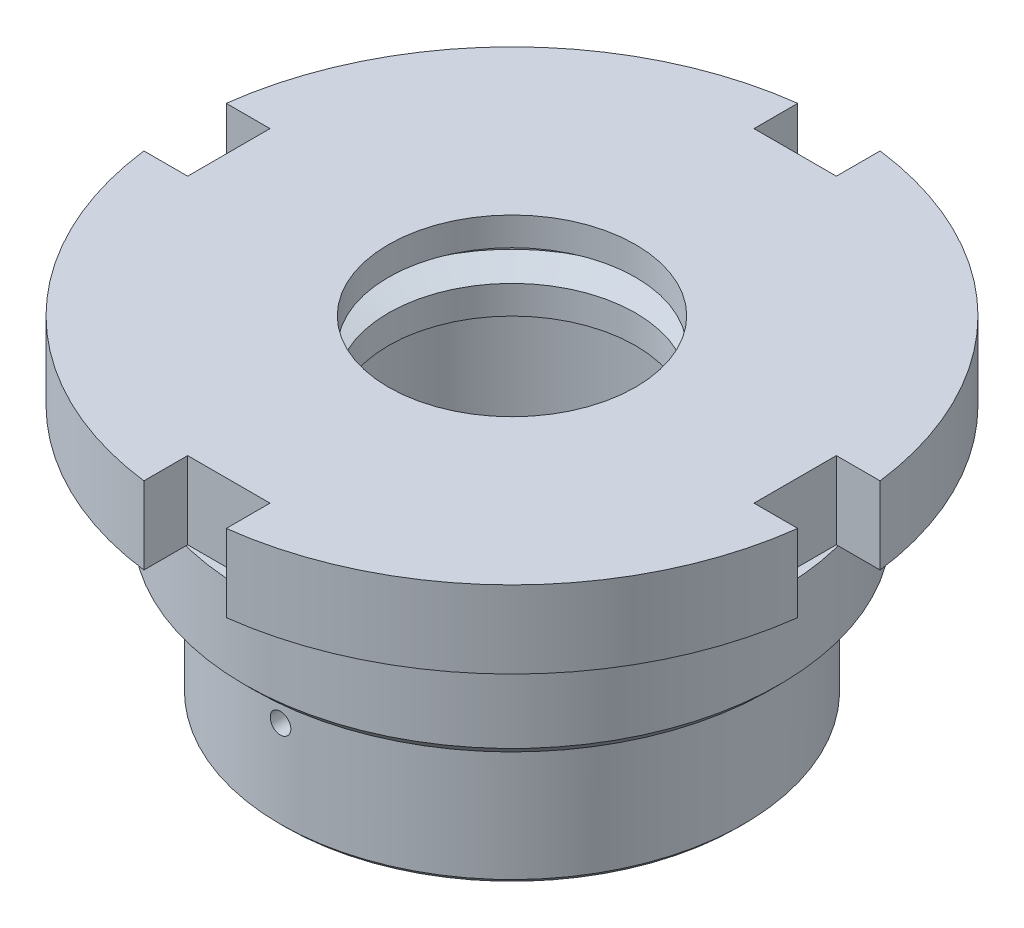
SolidWorks part; units mm, degrees
material "1023 Листовая углеродистая сталь (SS)"
ref_plane "Спереди" through (0, 0, 0) normal (0, 0, 1) x (1, 0, 0)
ref_plane "Сверху" through (0, 0, 0) normal (0, 1, 0) x (1, 0, 0)
ref_plane "Справа" through (0, 0, 0) normal (1, 0, 0) x (0, 0, -1)
ref_plane "Плоскость4" through (0, 0, 0) normal (0, 0, -1) x (-1, 0, 0)
sketch "Эскиз1" plane through (0, 0, 0) normal (0, 0, -1) x (-1, 0, 0)
  line L0 (-64, 49) -> (0, 49)
  line L1 (0, 49) -> (0, 64)
  line L2 (0, 64) -> (-64, 64)
  line L3 (-64, 64) -> (-64, 49)
  line L4 (0, 49) -> (0, 64) construction
revolve "Повернуть1" add sketch "Эскиз1" angle 360 about L4
sketch "Эскиз2" plane through (0, 64, 0) normal (0, 1, 0) x (-1, 0, 0)
  line L0 (63.498, 8) -> (55, 8)
  line L1 (55, 8) -> (55, -8)
  line L2 (55, -8) -> (63.498, -8)
  arc A0 (63.498, -8) -> (63.498, 8) centre (0, 0) ccw
extrude "Вырез-Вытянуть1" cut sketch "Эскиз2" against normal through all
sketch "Эскиз3" plane through (0, 64, 0) normal (0, 1, 0) x (-1, 0, 0)
  line L0 (8, -63.498) -> (8, -55)
  line L1 (8, -55) -> (-8, -55)
  line L2 (-8, -55) -> (-8, -63.498)
  arc A0 (-8, -63.498) -> (8, -63.498) centre (0, 0) ccw
extrude "Вырез-Вытянуть2" cut sketch "Эскиз3" against normal through all
sketch "Эскиз4" plane through (0, 64, 0) normal (0, 1, 0) x (-1, 0, 0)
  line L0 (-63.498, -8) -> (-55, -8)
  line L1 (-55, -8) -> (-55, 8)
  line L2 (-55, 8) -> (-63.498, 8)
  arc A0 (-63.498, 8) -> (-63.498, -8) centre (0, 0) ccw
extrude "Вырез-Вытянуть3" cut sketch "Эскиз4" against normal through all
sketch "Эскиз5" plane through (0, 64, 0) normal (0, 1, 0) x (-1, 0, 0)
  line L0 (-8, 63.498) -> (-8, 55)
  line L1 (-8, 55) -> (8, 55)
  line L2 (8, 55) -> (8, 63.498)
  arc A0 (8, 63.498) -> (-8, 63.498) centre (0, 0) ccw
extrude "Вырез-Вытянуть4" cut sketch "Эскиз5" against normal through all
sketch "Эскиз6" plane through (0, 0, 0) normal (0, 0, -1) x (-1, 0, 0)
  line L0 (-45, 0) -> (0, 0)
  line L1 (0, 0) -> (0, 49)
  line L2 (0, 49) -> (-48, 49)
  line L3 (-48, 49) -> (-48, 44)
  line L4 (-48, 44) -> (-52, 44)
  line L5 (-52, 44) -> (-52, 26)
  line L6 (-52, 26) -> (-45, 26)
  line L7 (-45, 26) -> (-45, 0)
  line L8 (0, 0) -> (0, 49) construction
revolve "Повернуть2" add sketch "Эскиз6" angle 360 about L8
sketch "Эскиз7" plane through (0, 0, 0) normal (0, 0, -1) x (-1, 0, 0)
  line L0 (-36, 0) -> (0, 0)
  line L1 (0, 0) -> (0, 64)
  line L2 (0, 64) -> (-24, 64)
  line L3 (-24, 64) -> (-24, 58.5)
  line L4 (-24, 58.5) -> (-30, 57.5)
  line L5 (-30, 57.5) -> (-30, 54)
  line L6 (-30, 54) -> (-24, 52.5)
  line L7 (-24, 52.5) -> (-24, 47)
  line L8 (-24, 47) -> (-36, 47)
  line L9 (-36, 47) -> (-36, 0)
  line L10 (0, 0) -> (0, 64) construction
revolve "Вырез-Повернуть1" cut sketch "Эскиз7" angle 360 about L10
ref_plane "Плоскость5" through (0, 0, -35.9444) normal (0, 0, 1) x (1, 0, 0)
hole_wizard "Диаметр отверстия Ø4.0 (4)1" positions "Эскиз9" profile "Эскиз8" hole size "Ø4.0" standard "Ansi Metric"
sketch "Эскиз9" plane through (0, 0, -35.9444) normal (0, 0, 1) x (1, 0, 0)
  point P0 (0, 18)
sketch "Эскиз8" plane through (0, 18, -35.9444) normal (1, 0, 0) x (0, -1, 0)
  line L0 (0, 0) -> (0, 27.5536)
  line L1 (0, 27.5536) -> (2, 27.5536)
  line L2 (2, 27.5536) -> (2, 0)
  line L5 (2, 0) -> (0, 0)
  line L11 (0, -6.35) -> (0, 107.95) construction
  dimension "Диаметр сквозного отверстия" = 4
  dimension "Глубина сквозного отверстия" = 27.5536
hole_wizard "Диаметр отверстия Ø4.0 (4)2" positions "Трехмерный эскиз1" profile "Эскиз10" hole size "Ø4.0" standard "Ansi Metric"
sketch3d "Трехмерный эскиз1"
  point P0 (0, 18, 45)
sketch "Эскиз10" plane through (0, 18, 45) normal (1, 0, 0) x (0, -1, 0)
  line L0 (0, 0) -> (0, 108.498)
  line L1 (0, 108.498) -> (2, 108.498)
  line L2 (2, 108.498) -> (2, 0)
  line L5 (2, 0) -> (0, 0)
  line L11 (0, -6.35) -> (0, 107.95) construction
  dimension "Диаметр сквозного отверстия" = 4
  dimension "Глубина сквозного отверстия" = 108.498
chamfer "Фаска1" distance 2 angle 45 1 edges at (0, 26, 52)
chamfer "Фаска2" distance 1 angle 45 1 edges at (0, 0, 45)
